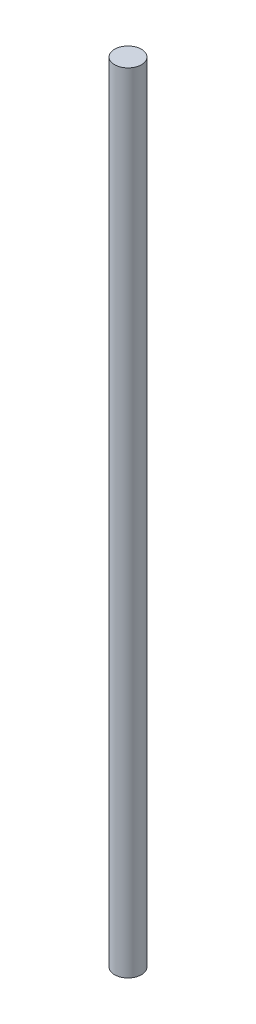
SolidWorks part; units mm, degrees
ref_plane "前视基准面" through (0, 0, 0) normal (0, 0, 1) x (1, 0, 0)
ref_plane "上视基准面" through (0, 0, 0) normal (0, 1, 0) x (1, 0, 0)
ref_plane "右视基准面" through (0, 0, 0) normal (1, 0, 0) x (0, 0, -1)
other "Configuration Table"
sketch "草图1" plane through (0, 0, 0) normal (0, 1, 0) x (1, 0, 0)
  circle A0 centre (0, 0) radius 4
extrude "凸台-拉伸1" add sketch "草图1" along normal blind 235
